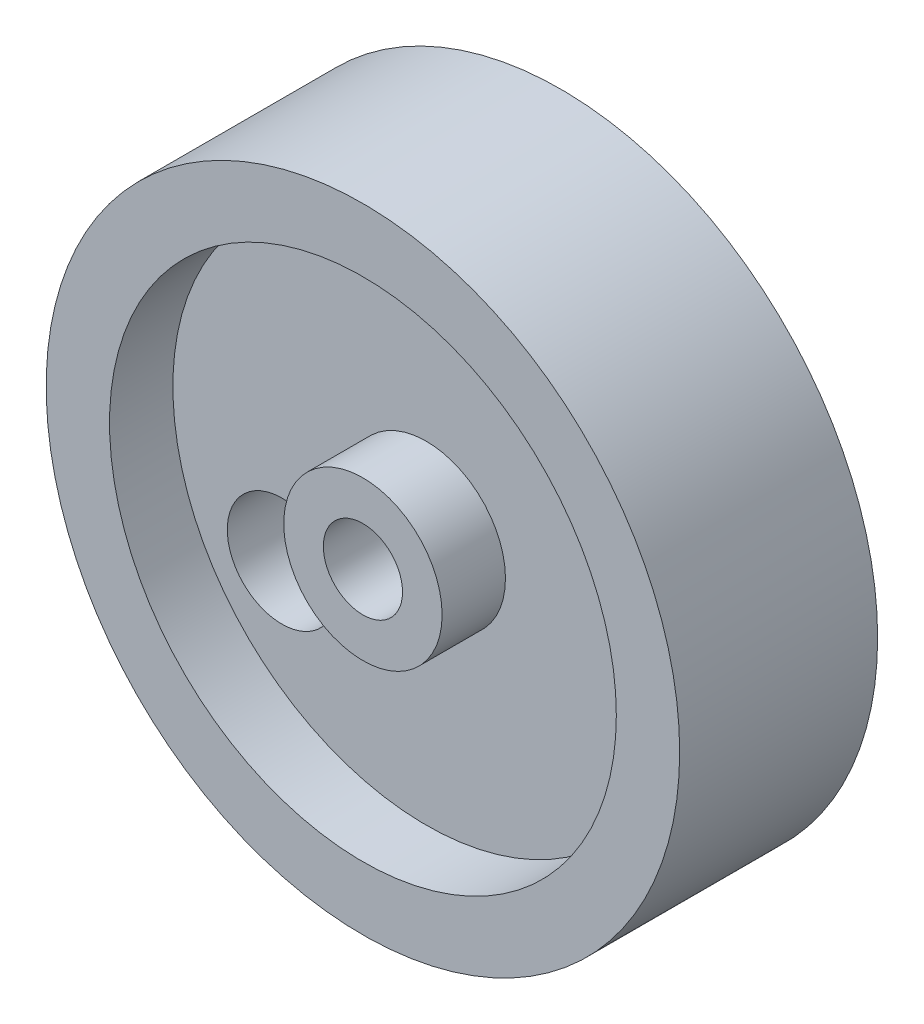
SolidWorks part; units mm, degrees
material "PP Copolymer"
ref_plane "Front Plane" through (0, 0, 0) normal (0, 0, 1) x (1, 0, 0)
ref_plane "Top Plane" through (0, 0, 0) normal (0, 1, 0) x (1, 0, 0)
ref_plane "Right Plane" through (0, 0, 0) normal (1, 0, 0) x (0, 0, -1)
sketch "Sketch1" plane through (0, 0, 0) normal (0, 0, 1) x (1, 0, 0)
  circle A0 centre (0, 0) radius 50.8
  circle A1 centre (0, 0) radius 6.35
  dimension "D1" = 101.6
  dimension "D2" = 12.7
extrude "Boss-Extrude1" add sketch "Sketch1" against normal mid plane 31.75
sketch "Sketch2" plane through (0, 0, 15.875) normal (0, 0, 1) x (1, 0, 0)
  circle A0 centre (0, 0) radius 12.7
  circle A1 centre (0, 0) radius 40.64
  dimension "D1" = 81.28
  dimension "D2" = 25.4
extrude "Cut-Extrude1" cut sketch "Sketch2" against normal blind 10.16
mirror "Mirror1" about plane through (0, 0, 0) normal (0, 0, 1) of "Cut-Extrude1"
sketch "Sketch3" plane through (0, 0, 5.715) normal (0, 0, 1) x (1, 0, 0)
  circle A0 centre (-23.1513, -15.5273) radius 8.7589
extrude "Cut-Extrude2" cut sketch "Sketch3" against normal up to next
